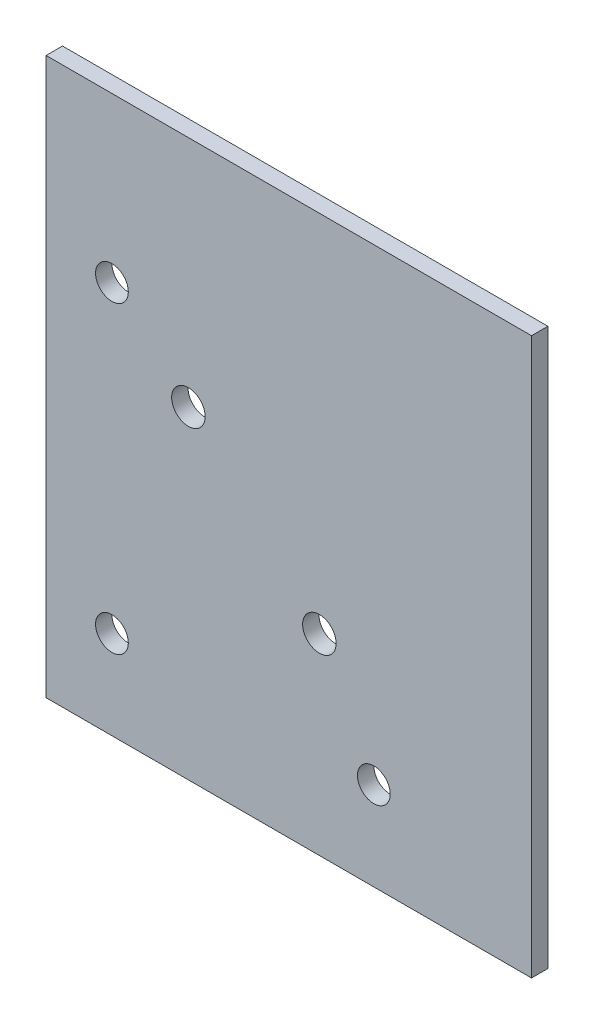
SolidWorks part; units mm, degrees
ref_plane "Front Plane" through (0, 0, 0) normal (0, 0, 1) x (1, 0, 0)
ref_plane "Top Plane" through (0, 0, 0) normal (0, 1, 0) x (1, 0, 0)
ref_plane "Right Plane" through (0, 0, 0) normal (1, 0, 0) x (0, 0, -1)
sketch "Sketch1" plane through (0, 0, 0) normal (0, 0, 1) x (1, 0, 0)
  line L1 (5.1833, 100.7604) -> (-88.9667, 100.7604)
  line L2 (5.1833, 100.7604) -> (5.1833, 208.6503)
  line L3 (5.1833, 208.6503) -> (-88.9667, 208.6503)
  line L4 (-88.9667, 100.7604) -> (-88.9667, 208.6503)
  line L5 (-23.2675, 150.6967) -> (-48.6675, 150.6967) construction
  line L6 (-48.6675, 201.4967) -> (-48.6675, 150.6967) construction
  circle A3 centre (-76.2, 117.9286) radius 3.175
  circle A4 centre (-25.4, 117.9286) radius 3.175
  circle A5 centre (-76.2, 176.8929) radius 3.175
  circle A6 centre (-61.3675, 163.3967) radius 3.2512
  circle A7 centre (-35.9675, 137.9967) radius 3.2512
  dimension "D1" = 6.5024
  dimension "D2" = 12.7
  dimension "D3" = 12.7
  dimension "D4" = 12.7
  dimension "D5" = 12.7
extrude "Boss-Extrude1" add sketch "Sketch1" along normal blind 3.175
equation "\"80/20 to Center Hole\"= .64in"
equation "\"80/20 from Edge\"= 0.5in"
